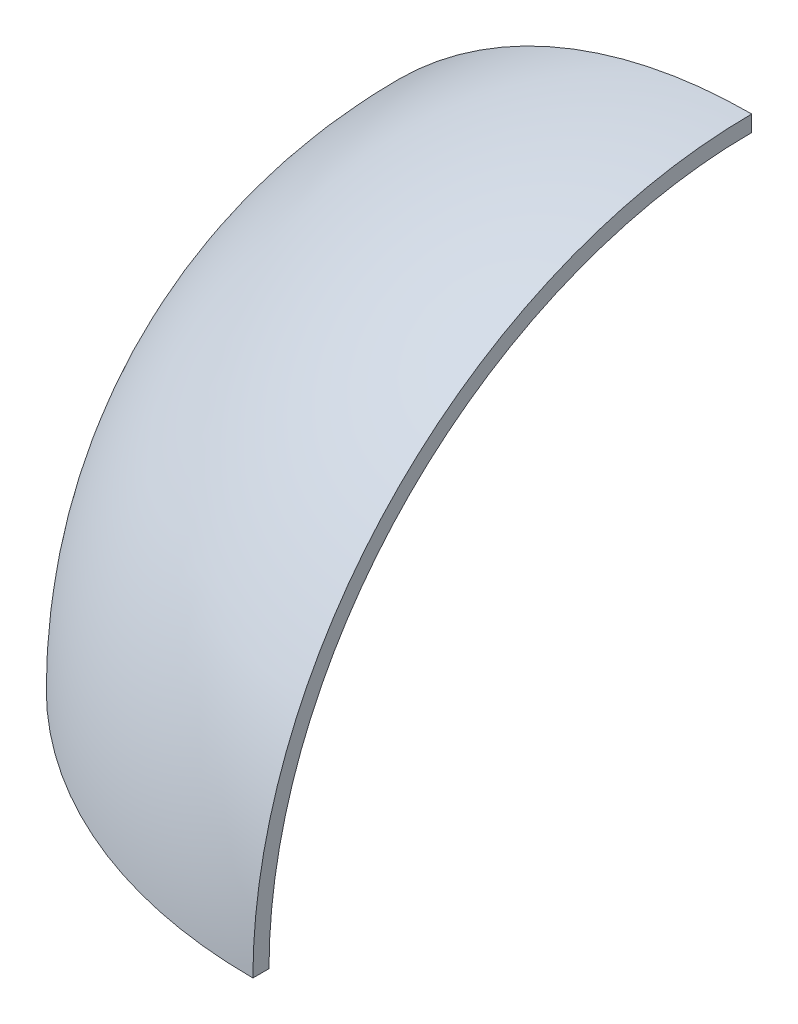
SolidWorks part; units mm, degrees
ref_plane "前视基准面" through (0, 0, 0) normal (0, 0, 1) x (1, 0, 0)
ref_plane "上视基准面" through (0, 0, 0) normal (0, 1, 0) x (1, 0, 0)
ref_plane "右视基准面" through (0, 0, 0) normal (1, 0, 0) x (0, 0, -1)
sketch "草图2" plane through (0, 0, 0) normal (0, 0, 1) x (1, 0, 0)
  line L4 (0, 30) -> (0, 31)
  line L5 (-30, 0) -> (-31, 0)
  line L7 (0, 0) -> (-30, 0) construction
  line L8 (0, 0) -> (0, 30) construction
  line L9 (1, -1) -> (1, 30.9839) construction
  line L10 (1, -1) -> (-30.9839, -1) construction
  arc A0 (0, 30) -> (-30, 0) centre (0, 0) ccw
  arc A1 (0, 31) -> (-31, 0) centre (0, 0) ccw
  arc A3 (1, 30.9839) -> (-30.9839, -1) centre (0, 0) ccw construction
  dimension "D1" = 30
  dimension "D2" = 1
revolve "旋转1" add sketch "草图2" angle 90 about L4
